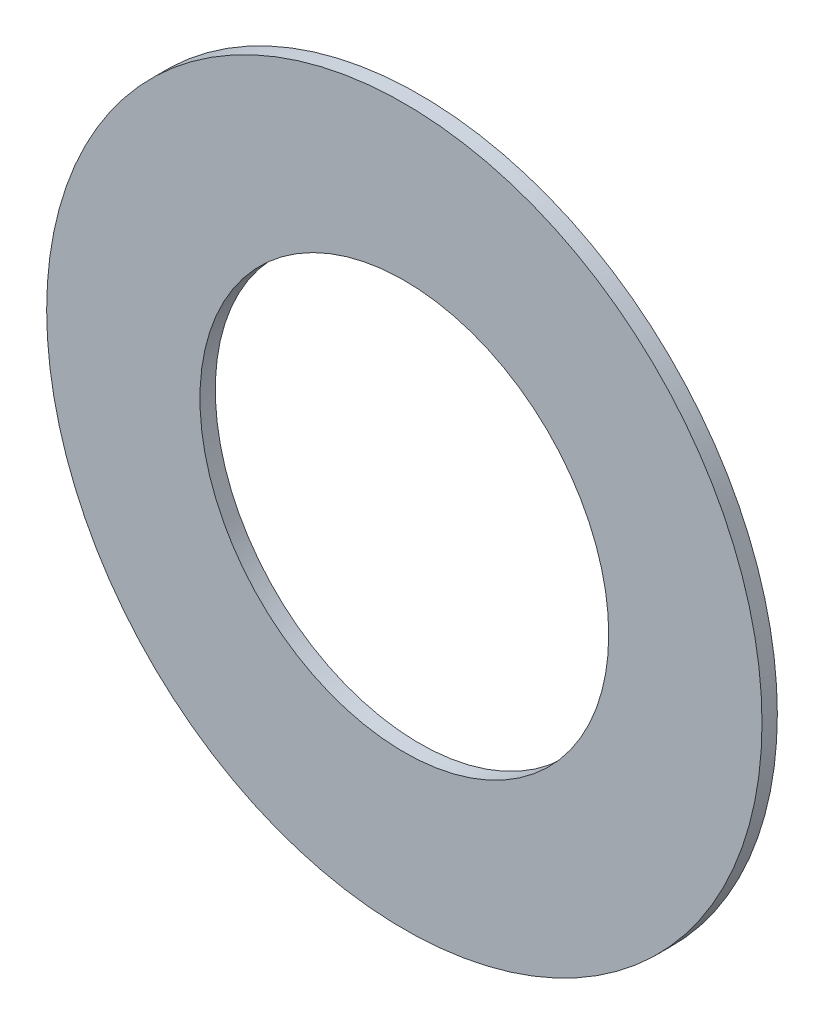
SolidWorks part; units mm, degrees
ref_plane "Front Plane" through (0, 0, 0) normal (0, 0, 1) x (1, 0, 0)
ref_plane "Top Plane" through (0, 0, 0) normal (0, 1, 0) x (1, 0, 0)
ref_plane "Right Plane" through (0, 0, 0) normal (1, 0, 0) x (0, 0, -1)
sketch "Sketch1" plane through (0, 0, 0) normal (0, 0, 1) x (1, 0, 0)
  circle A0 centre (0, 0) radius 4
  circle A1 centre (0, 0) radius 7
  dimension "D1" = 8
  dimension "D2" = 14
extrude "Boss-Extrude1" add sketch "Sketch1" along normal blind 0.3
